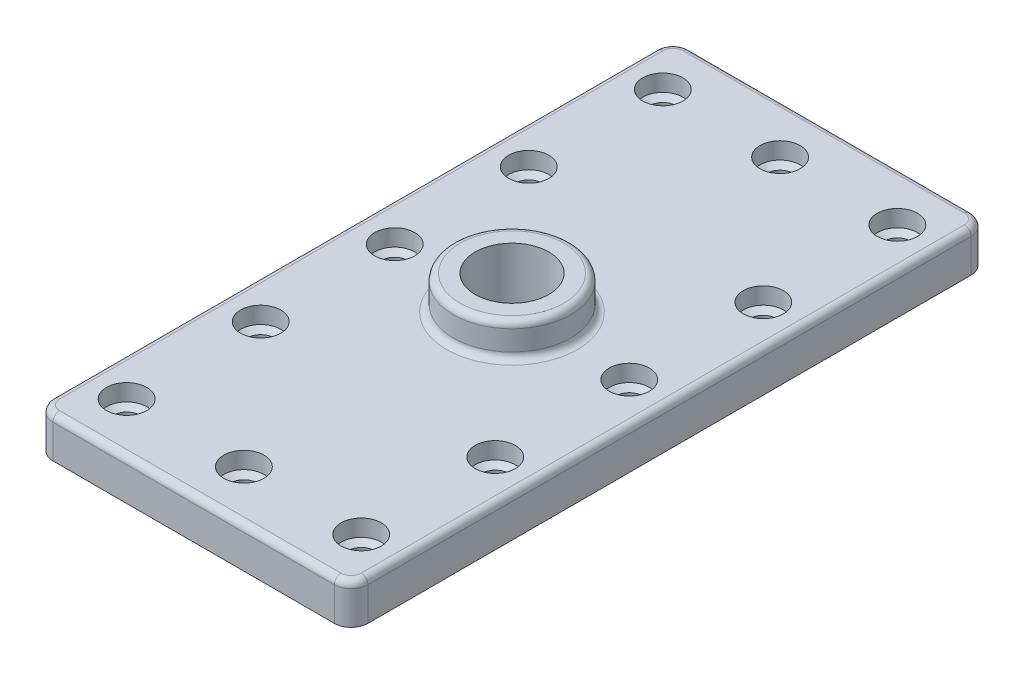
SolidWorks part; units mm, degrees
ref_plane "Front" through (0, 0, 0) normal (0, 0, 1) x (1, 0, 0)
ref_plane "Top" through (0, 0, 0) normal (0, 1, 0) x (1, 0, 0)
ref_plane "Right" through (0, 0, 0) normal (1, 0, 0) x (0, 0, -1)
sketch "Sketch1" plane through (0, 0, 0) normal (0, 1, 0) x (1, 0, 0)
  line L0 (-47, 95) -> (47, -95) construction
  line L1 (-47, -95) -> (47, -95)
  line L2 (-47, -95) -> (-47, 95)
  line L3 (-47, 95) -> (47, 95)
  line L4 (47, -95) -> (47, 95)
  dimension "D1" = 190
  dimension "D2" = 94
extrude "plate" add sketch "Sketch1" along normal blind 12
sketch "Sketch2" plane through (0, 12, 0) normal (0, 1, 0) x (-1, 0, 0)
  circle A0 centre (0, 0) radius 17.5
  dimension "D1" = 35
extrude "boss" add sketch "Sketch2" along normal blind 10
sketch "Sketch3" plane through (0, 22, 0) normal (0, 1, 0) x (-1, 0, 0)
  circle A0 centre (0, 0) radius 11
  dimension "D1" = 22
extrude "center hole" cut sketch "Sketch3" against normal through all
hole_wizard "pattern hole" positions "Sketch5" profile "Sketch4" legacy end condition through all
sketch "Sketch5" plane through (0, 12, 0) normal (0, 1, 0) x (-1, 0, 0)
  line L0 (47, 95) -> (-47, 95) construction
  line L1 (47, -95) -> (47, 95) construction
  point P0 (35, 80)
  dimension "D1" = 15
  dimension "D2" = 12
sketch "Sketch4" plane through (-35, 12, 80) normal (1, 0, 0) x (0, 0, 1)
  line L0 (0, 0) -> (0, 12)
  line L1 (0, 12) -> (4, 12)
  line L2 (4, 12) -> (4, 6.2017)
  line L3 (4, 6.2017) -> (6, 5)
  line L4 (6, 5) -> (6, 0)
  line L5 (6, 0) -> (0, 0)
  line L6 (0, -6.13) -> (0, 109.2824) construction
  line L7 (-4, 6.2017) -> (-6, 5) construction
  line L8 (0, 12) -> (-4, 12) construction
  dimension "Diameter" = 8
  dimension "Depth" = 12
  dimension "C-Drill Diameter" = 12
  dimension "C-Drill Depth" = 5
  dimension "C-Drill Angle" = 118
fillet "R5" radius 5 4 edges at (-47, 6, -95) (47, 6, -95) (47, 6, 95) (-47, 6, 95)
fillet "R2" radius 2 10 edges at (0, 12, -17.5) (0, 22, 17.5) (47, 12, 0) (0, 12, 95) (-47, 12, 0) (0, 12, -95) (45.5355, 12, -93.5355) (-45.5355, 12, -93.5355) (-45.5355, 12, 93.5355) (45.5355, 12, 93.5355)
pattern_linear "LPattern1" count 5 spacing 40 along (0, 0, -1) count 3 spacing 35 along (1, 0, 0) skipping (1, 1), (2, 1), (3, 1) of "pattern hole"
